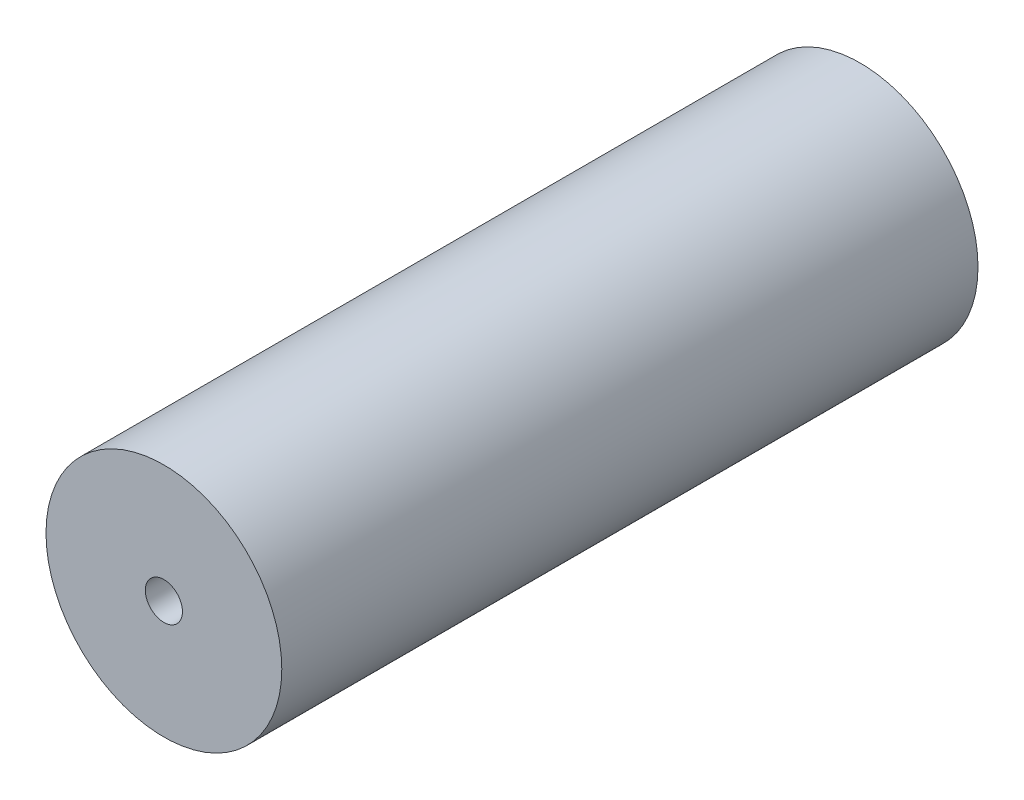
SolidWorks part; units mm, degrees
ref_plane "Front Plane" through (0, 0, 0) normal (0, 0, 1) x (1, 0, 0)
ref_plane "Top Plane" through (0, 0, 0) normal (0, 1, 0) x (1, 0, 0)
ref_plane "Right Plane" through (0, 0, 0) normal (1, 0, 0) x (0, 0, -1)
sketch "Sketch1" plane through (0, 0, 0) normal (0, 0, 1) x (1, 0, 0)
  circle A0 centre (0, 0) radius 25.4
  dimension "D1" = 50.8
extrude "Boss-Extrude1" add sketch "Sketch1" along normal blind 150 contours A0
ref_plane "Plane1" through (0, 0, 150) normal (0, 0, 1) x (1, 0, 0)
sketch "Sketch2" plane through (0, 0, 150) normal (0, 0, 1) x (1, 0, 0)
  circle A0 centre (0, 0) radius 4
  dimension "D1" = 8
extrude "Cut-Extrude1" cut sketch "Sketch2" against normal blind 25
